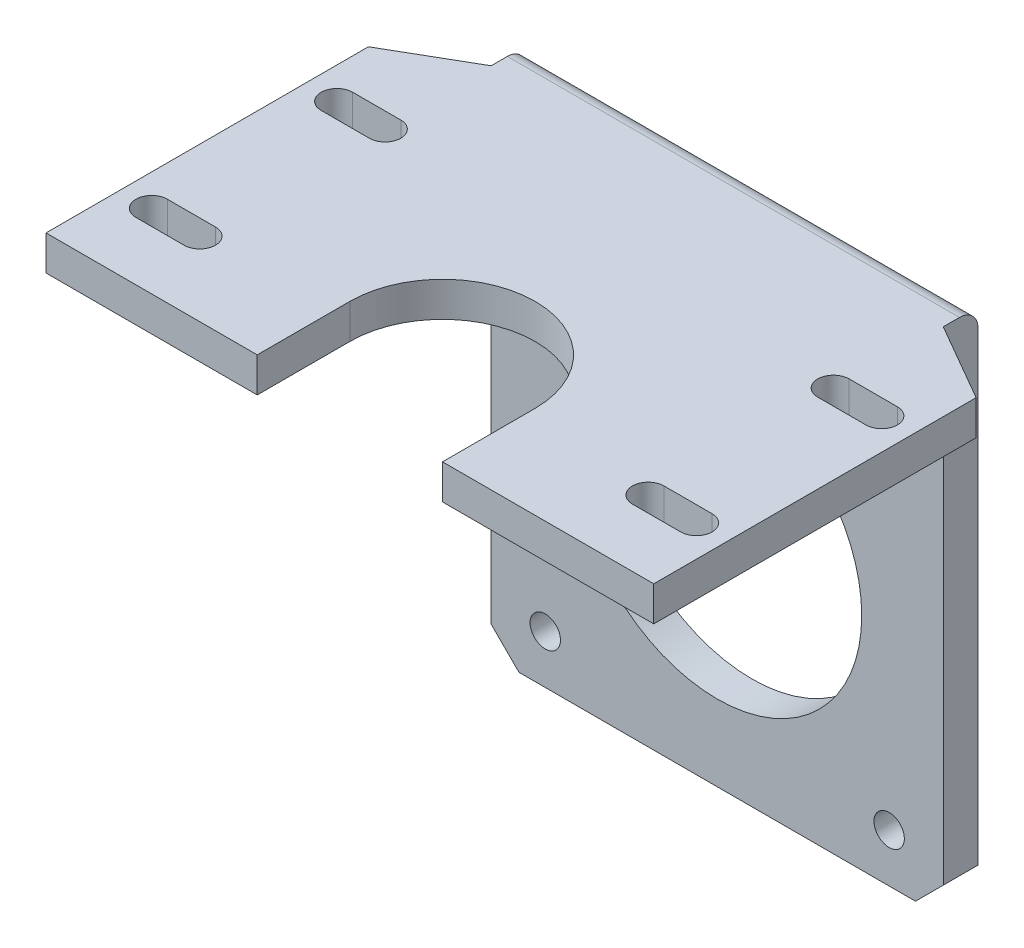
SolidWorks part; units mm, degrees
ref_plane "Front Plane" through (0, 0, 0) normal (0, 0, 1) x (1, 0, 0)
ref_plane "Top Plane" through (0, 0, 0) normal (0, 1, 0) x (1, 0, 0)
ref_plane "Right Plane" through (0, 0, 0) normal (1, 0, 0) x (0, 0, -1)
sketch "Sketch1" plane through (0, 0, 0) normal (0, 0, 1) x (1, 0, 0)
  line L0 (23.5712, 23.5712) -> (-23.5712, 23.5712) construction
  line L1 (-27.178, -30.226) -> (27.178, -30.226)
  line L2 (0, 0) -> (-9.724, 0) construction
  line L3 (0, 0) -> (0, -4.8475) construction
  line L4 (-30.988, -26.416) -> (-30.988, 39.878)
  line L5 (-30.988, 39.878) -> (30.988, 39.878)
  line L6 (30.988, -26.416) -> (30.988, 39.878)
  line L9 (23.5712, -23.5712) -> (-23.5712, -23.5712) construction
  line L10 (23.5712, -23.5712) -> (23.5712, 23.5712) construction
  line L11 (-23.5712, -23.5712) -> (-23.5712, 23.5712) construction
  line L16 (-30.988, -26.416) -> (-27.178, -30.226)
  line L17 (30.988, -26.416) -> (27.178, -30.226)
  circle A0 centre (0, 0) radius 19.812
  circle A1 centre (-23.5712, 23.5712) radius 2.0828
  circle A2 centre (23.5712, 23.5712) radius 2.0828
  circle A3 centre (23.5712, -23.5712) radius 2.0828
  circle A4 centre (-23.5712, -23.5712) radius 2.0828
  dimension "D1" = 39.624
  dimension "D2" = 70.104
  dimension "D4" = 4.1656
  dimension "D3" = 61.976
extrude "Boss-Extrude1" add sketch "Sketch1" along normal blind 4.7625
ref_plane "Plane1" through (0, 39.878, 0) normal (0, 1, 0) x (-1, 0, 0)
sketch "Sketch4" plane through (0, 39.878, 0) normal (0, 1, 0) x (-1, 0, 0)
  line L0 (0, 4.7625) -> (0, 30.7793) construction
  line L1 (12.7, 55.118) -> (41.656, 55.118)
  line L2 (-41.656, 55.118) -> (-12.7, 55.118)
  line L3 (41.656, 10.9217) -> (41.656, 55.118)
  line L4 (-41.656, 10.9217) -> (-41.656, 55.118)
  line L5 (-12.7, 55.118) -> (-12.7, 42.418)
  line L6 (-34.036, 55.118) -> (-34.036, 24.2137) construction
  line L7 (12.7, 42.418) -> (12.7, 55.118)
  line L8 (34.036, 55.118) -> (34.036, 24.2137) construction
  line L9 (-39.497, 44.958) -> (-28.575, 44.958) construction
  line L10 (-30.734, 47.117) -> (-37.338, 47.117)
  line L11 (-37.338, 42.799) -> (-30.734, 42.799)
  line L12 (39.497, 19.558) -> (28.575, 19.558) construction
  line L13 (-30.734, 21.717) -> (-37.338, 21.717)
  line L14 (39.497, 44.958) -> (28.575, 44.958) construction
  line L15 (-39.497, 19.558) -> (-28.575, 19.558) construction
  line L16 (-37.338, 17.399) -> (-30.734, 17.399)
  line L17 (37.338, 17.399) -> (30.734, 17.399)
  line L18 (30.734, 21.717) -> (37.338, 21.717)
  line L19 (37.338, 42.799) -> (30.734, 42.799)
  line L20 (30.734, 47.117) -> (37.338, 47.117)
  line L21 (-30.988, 4.7625) -> (-41.656, 10.9217)
  line L22 (-30.988, 4.7625) -> (-30.988, 0)
  line L23 (-30.988, 0) -> (30.988, 0)
  line L24 (30.988, 0) -> (30.988, 4.7625)
  line L25 (30.988, 4.7625) -> (41.656, 10.9217)
  arc A0 (-37.338, 21.717) -> (-37.338, 17.399) centre (-37.338, 19.558) ccw
  arc A1 (-30.734, 47.117) -> (-30.734, 42.799) centre (-30.734, 44.958) cw
  arc A2 (-12.7, 42.418) -> (12.7, 42.418) centre (0, 42.418) ccw
  arc A3 (-37.338, 47.117) -> (-37.338, 42.799) centre (-37.338, 44.958) ccw
  arc A4 (30.734, 21.717) -> (30.734, 17.399) centre (30.734, 19.558) ccw
  arc A5 (-30.734, 21.717) -> (-30.734, 17.399) centre (-30.734, 19.558) cw
  arc A6 (37.338, 47.117) -> (37.338, 42.799) centre (37.338, 44.958) cw
  arc A7 (30.734, 47.117) -> (30.734, 42.799) centre (30.734, 44.958) ccw
  arc A8 (37.338, 21.717) -> (37.338, 17.399) centre (37.338, 19.558) cw
  dimension "D1" = 68.072
  dimension "D2" = 83.312
  dimension "D3" = 12.7
extrude "Boss-Extrude2" add sketch "Sketch4" against normal blind 4.7625
fillet "Fillet1" radius 2.54 2 edges at (0, 35.1155, 4.7625) (0, 39.878, 0)
sketch "Sketch5" plane through (0, 39.878, 0) normal (0, 1, 0) x (-1, 0, 0)
  line L0 (0, 0) -> (0, 21.8714) construction
  circle A0 centre (-34.036, 44.958) radius 2.159 construction
  circle A1 centre (-34.036, 19.558) radius 2.159 construction
  circle A2 centre (34.036, 19.558) radius 2.159 construction
  circle A3 centre (34.036, 44.958) radius 2.159 construction
